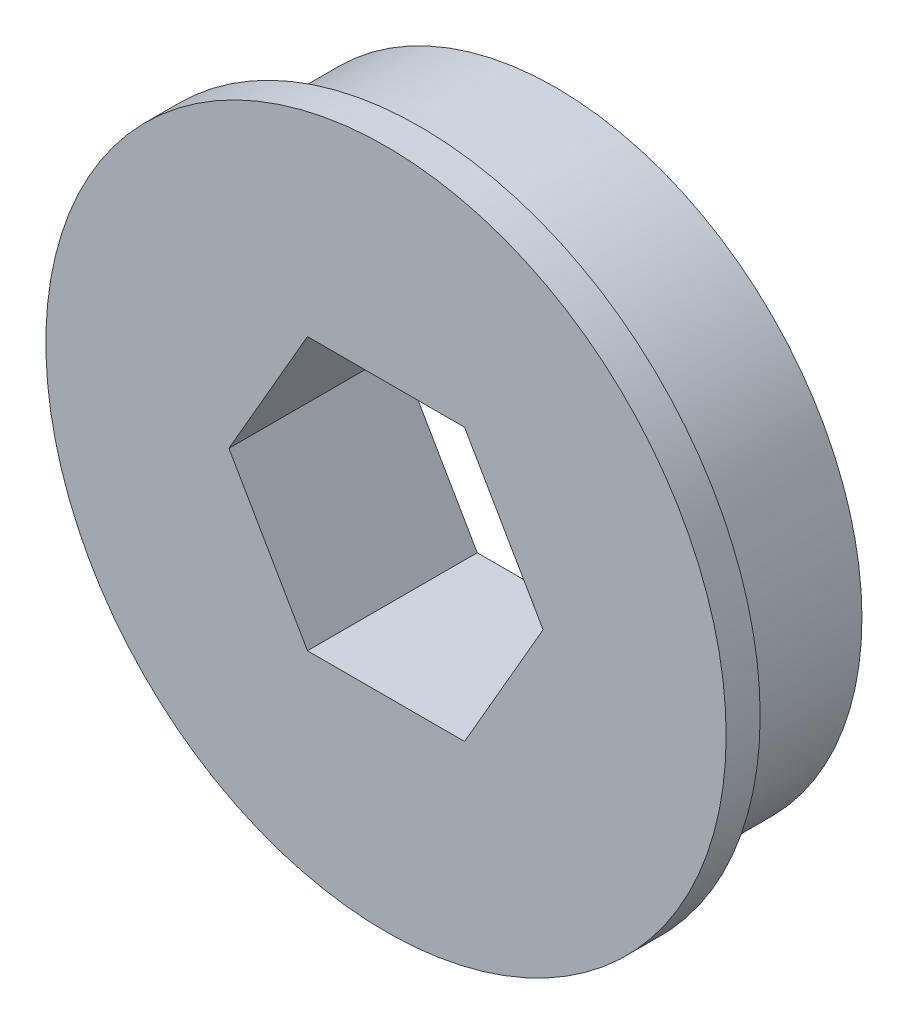
SolidWorks part; units mm, degrees
ref_plane "Front Plane" through (0, 0, 0) normal (0, 0, 1) x (1, 0, 0)
ref_plane "Top Plane" through (0, 0, 0) normal (0, 1, 0) x (1, 0, 0)
ref_plane "Right Plane" through (0, 0, 0) normal (1, 0, 0) x (0, 0, -1)
sketch "Sketch1" plane through (0, 0, 0) normal (1, 0, 0) x (0, 0, -1)
  line L0 (0, 15.875) -> (0, 0)
  line L1 (0, 0) -> (7.9248, 0)
  line L2 (7.9248, 0) -> (7.9248, 14.2875)
  line L3 (7.9248, 14.2875) -> (1.5875, 14.2875)
  line L4 (1.5875, 14.2875) -> (1.5875, 15.875)
  line L5 (1.5875, 15.875) -> (0, 15.875)
  dimension "D1" = 1.5875
  dimension "D2" = 7.9248
  dimension "D3" = 14.2875
revolve "Revolve1" add sketch "Sketch1" angle 360 about L1
sketch "Sketch2" plane through (0, 0, 0) normal (0, 0, 1) x (1, 0, 0)
  line L1 (7.3323, 0) -> (3.6662, 6.35)
  line L2 (3.6662, 6.35) -> (-3.6662, 6.35)
  line L3 (-3.6662, 6.35) -> (-7.3323, 0)
  line L4 (-7.3323, 0) -> (-3.6662, -6.35)
  line L5 (-3.6662, -6.35) -> (3.6662, -6.35)
  line L6 (3.6662, -6.35) -> (7.3323, 0)
  circle A0 centre (0, 0) radius 6.35 construction
  dimension "D1" = 12.7
extrude "Cut-Extrude1" cut sketch "Sketch2" against normal through all
